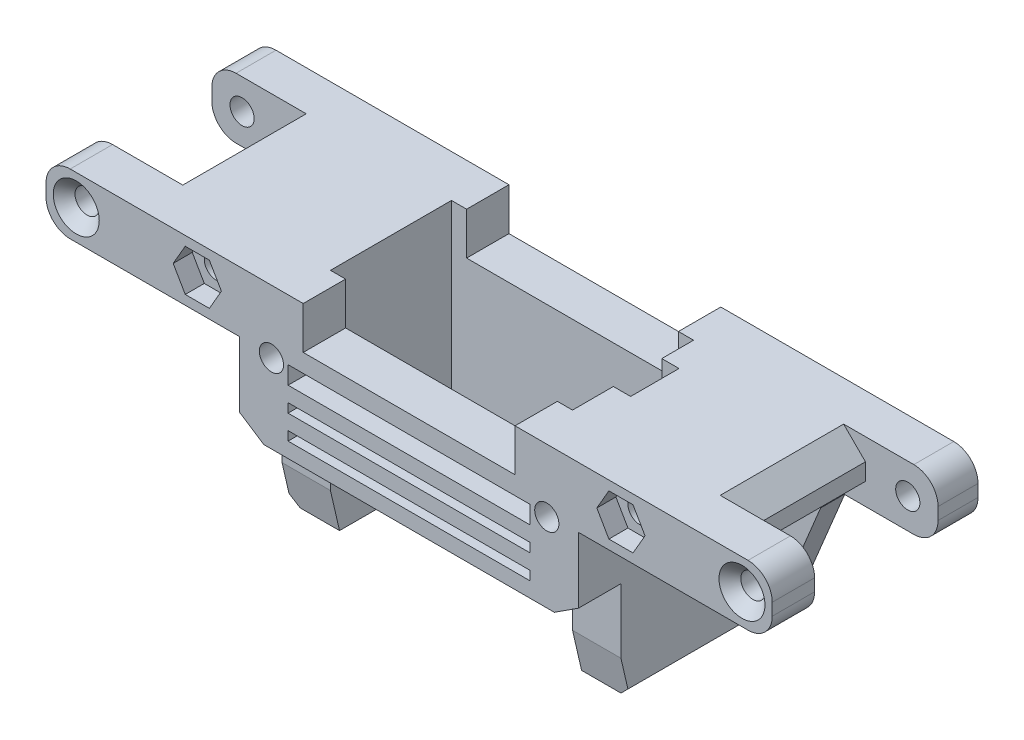
SolidWorks part; units mm, degrees
ref_plane "Front Plane" through (0, 0, 0) normal (0, 0, 1) x (1, 0, 0)
ref_plane "Top Plane" through (0, 0, 0) normal (0, 1, 0) x (1, 0, 0)
ref_plane "Right Plane" through (0, 0, 0) normal (1, 0, 0) x (0, 0, -1)
sketch "Sketch1" plane through (0, 0, 0) normal (0, 1, 0) x (1, 0, 0)
  line L0 (-60, 17) -> (-60, 10)
  line L1 (-60, 10) -> (-28, 10)
  line L2 (-28, 10) -> (-28, -10)
  line L3 (-28, 0) -> (-20, 0)
  line L4 (-20, -10) -> (-20, 10)
  line L5 (-20, 10) -> (20, 10)
  line L6 (20, 10) -> (20, -10)
  line L7 (20, 0) -> (28, 0)
  line L8 (28, -10) -> (28, 10)
  line L9 (28, 10) -> (60, 10)
  line L10 (60, 10) -> (60, 17)
  line L11 (60, 17) -> (-60, 17)
  line L12 (60, -17) -> (-60, -17)
  line L13 (60, -10) -> (60, -17)
  line L14 (28, -10) -> (60, -10)
  line L15 (-20, -10) -> (20, -10)
  line L16 (-60, -10) -> (-28, -10)
  line L17 (-60, -17) -> (-60, -10)
  point P0 (0, 10)
  point P16 (0, 17)
  dimension "D1" = 40
  dimension "D2" = 120
  dimension "D3" = 8
  dimension "D4" = 8
  dimension "D5" = 10
  dimension "D6" = 7
extrude "Boss-Extrude1" add sketch "Sketch1" along normal blind 10 contours L10 L11 L0 L1 L2 L3 L4 L5 L6 L7 L8 L9 | L17 L12 L13 L14 L8 L7 L6 L15 L4 L3 L2 L16
hole_wizard "CSK for M4 Flat Head Machine Screw1" positions "Sketch3" profile "Sketch4" countersink size "M4" standard "ANSI Metric"
sketch "Sketch3" plane through (0, 0, 17) normal (0, 0, 1) x (1, 0, 0)
  line L0 (60, 10) -> (60, 0) construction
  line L1 (-60, 10) -> (-60, 0) construction
  point P0 (-55, 5)
  point P3 (55, 5)
  point P14 (-60, 5)
  dimension "D1" = 5
  dimension "D2" = 5
sketch "Sketch4" plane through (-55, 5, 17) normal (1, 0, 0) x (0, -1, 0)
  line L0 (0, 0) -> (0, 55)
  line L1 (0, 55) -> (2, 53.7983)
  line L2 (2, 53.7983) -> (2, 1.8)
  line L3 (2, 1.8) -> (3.8, 0)
  line L5 (3.8, 0) -> (0, 0)
  line L6 (-2, 1.8) -> (-3.8, 0) construction
  line L10 (0, 55) -> (-2, 53.7983) construction
  line L11 (0, -6.35) -> (0, 107.95) construction
  dimension "Hole Dia." = 4
  dimension "Hole Depth" = 55
  dimension "Near C'Sink Dia." = 7.6
  dimension "Near C'Sink Angle" = 90
  dimension "Drill Angle" = 118
fillet "Fillet1" radius 4 8 edges at (60, 0, 13.5) (60, 10, 13.5) (60, 0, -13.5) (60, 10, -13.5) (-60, 0, -13.5) (-60, 10, -13.5) (-60, 0, 13.5) (-60, 10, 13.5)
sketch "Sketch5" plane through (0, 0, 0) normal (0, -1, 0) x (1, 0, 0)
  line L0 (-28, 10) -> (-28, -17)
  line L1 (-28, -10) -> (-28, 10) construction
  line L2 (-56, 10) -> (-28, 10) construction
  line L3 (56, -17) -> (-56, -17) construction
  line L4 (-28, -17) -> (28, -17)
  line L5 (28, -17) -> (28, 10)
  line L6 (28, 10) -> (56, 10) construction
  line L7 (28, 10) -> (28, -10) construction
  line L8 (-28, 10) -> (-20, 10)
  line L9 (-20, 10) -> (-20, -10) construction
  line L10 (-20, 10) -> (20, 10) construction
  line L11 (-20, 10) -> (-20, -10)
  line L12 (-20, -10) -> (20, -10) construction
  line L13 (-20, -10) -> (20, -10)
  line L14 (20, -10) -> (20, 10)
  line L15 (20, -10) -> (20, 10) construction
  line L16 (20, 10) -> (28, 10)
extrude "Boss-Extrude2" add sketch "Sketch5" along normal blind 28
sketch "Sketch6" plane through (0, 0, 10) normal (0, 0, 1) x (1, 0, 0)
  line L0 (-28, -28) -> (28, -28)
  line L1 (-28, -28) -> (-28, 0) construction
  line L2 (-20, -28) -> (-28, -28) construction
  line L3 (28, -28) -> (20, -28) construction
  line L4 (28, -28) -> (28, 0)
  line L5 (56, 0) -> (-56, 0) construction
  line L6 (28, -28) -> (28, 0) construction
  line L7 (28, 0) -> (20, 0)
  line L8 (20, 0) -> (20, -23.44)
  line L9 (20, -23.44) -> (-20, -23.44)
  line L10 (-20, -28) -> (-20, 0) construction
  line L11 (-20, -23.44) -> (-20, 0)
  line L12 (-20, 0) -> (-28, 0)
  line L13 (20, -28) -> (20, 0) construction
  line L14 (-28, 0) -> (-28, -28)
  line L15 (-20, -21.44) -> (20, -21.44)
  line L16 (20, -21.44) -> (20, -18.94)
  line L17 (20, -18.94) -> (-20, -18.94)
  line L18 (-20, -18.94) -> (-20, -21.44)
  line L19 (-20, -14.94) -> (-20, -17.44)
  line L20 (-20, -17.44) -> (20, -17.44)
  line L21 (20, -17.44) -> (20, -14.94)
  line L22 (20, -14.94) -> (-20, -14.94)
  line L23 (-20, -10.94) -> (-20, -13.44)
  line L24 (-20, -13.44) -> (20, -13.44)
  line L25 (20, -13.44) -> (20, -10.94)
  line L26 (20, -10.94) -> (-20, -10.94)
  line L27 (-20, -6.94) -> (-20, -9.44)
  line L28 (-20, -9.44) -> (20, -9.44)
  line L29 (20, -9.44) -> (20, -6.94)
  line L30 (20, -6.94) -> (-20, -6.94)
  line L31 (-20, -2.94) -> (-20, -5.44)
  line L32 (-20, -5.44) -> (20, -5.44)
  line L33 (20, -5.44) -> (20, -2.94)
  line L34 (20, -2.94) -> (-20, -2.94)
  dimension "D1" = 4.56
  dimension "D2" = 2
  dimension "D3" = 2.5
  dimension "D4" = 5
extrude "Boss-Extrude3" add sketch "Sketch6" along normal up to surface (7 mm away) contours L8 L17 L11 L15 | L8 L22 L11 L20 | L8 L26 L11 L24 | L8 L30 L11 L28 | L8 L34 L11 L32 up to face at (-51.2, 5, 17)
sketch "Sketch7" plane through (0, 0, -10) normal (0, 0, 1) x (1, 0, 0)
  line L0 (28, 10) -> (56, 10) construction
  line L1 (28, 10) -> (48, 10)
  line L2 (28, 10) -> (28, 0)
  line L3 (28, 0) -> (48, 0)
  line L4 (48, 10) -> (48, 0)
  line L5 (28, 10) -> (28, 0) construction
  line L6 (28, 0) -> (56, 0) construction
  line L7 (-56, 10) -> (-28, 10) construction
  line L8 (-28, 10) -> (-48, 10)
  line L9 (-28, 10) -> (-28, 0)
  line L10 (-28, 0) -> (-48, 0)
  line L11 (-48, 10) -> (-48, 0)
  line L12 (-28, 10) -> (-28, 0) construction
  line L13 (-56, 0) -> (-28, 0) construction
  dimension "D1" = 20
  dimension "D2" = 20
extrude "Boss-Extrude4" add sketch "Sketch7" along normal up to surface (20 mm away) up to face at (53, 5, 10)
chamfer "Chamfer1" distance 3.6 4 edges at (48, 0, 0) (48, 10, 0) (-48, 10, 0) (-48, 0, 0)
sketch "Sketch9" plane through (-28, 0, 0) normal (-1, 0, 0) x (0, 0, 1)
  line L0 (-13, 0) -> (-13, -28)
  line L1 (17, 0) -> (-17, 0) construction
  line L2 (17, -28) -> (-17, -28) construction
  line L3 (-13, -28) -> (-17, -28)
  line L4 (-17, -28) -> (-17, 0) construction
  line L5 (-17, -28) -> (-17, 0)
  line L6 (-17, 0) -> (-13, 0)
  dimension "D1" = 4
extrude "Boss-Extrude5" add sketch "Sketch9" against normal blind 76 from offset 10
chamfer "Chamfer2" distance 11.5 angle 45 2 edges at (38, -28, -15) (-38, -28, -15)
sketch "Sketch10" plane through (0, -28, 0) normal (0, -1, 0) x (1, 0, 0)
  line L0 (-28, 17) -> (-28, 10)
  line L1 (-26.5, 17) -> (26.5, 17) construction
  line L2 (-28, 10) -> (28, 10)
  line L3 (28, 10) -> (28, 17)
  line L4 (28, 17) -> (-28, 17)
  line L5 (-28, -13) -> (-28, 17) construction
  line L6 (28, 17) -> (28, -13) construction
  line L7 (-20, 10) -> (20, 10) construction
extrude "Cut-Extrude1" cut sketch "Sketch10" against normal up to surface (14.56 mm away) up to face at (0, -13.44, 13.5)
chamfer "Chamfer3" distance 1.5 angle 77 2 edges at (23.25, -28, 10) (-23.25, -28, 10)
hole_wizard "CSK for M4 Flat Head Machine Screw2" positions "Sketch11" profile "Sketch12" countersink size "M4" standard "ANSI Metric"
sketch "Sketch11" plane through (-695.683, 1385.2473, -21) normal (0, 0, -1) x (-1, 0, 0)
  point P0 (-730.683, -1380.2473)
  point P2 (-660.683, -1380.2473)
sketch "Sketch12" plane through (35, 5, -21) normal (1, 0, 0) x (0, 1, 0)
  line L0 (0, 0) -> (0, 40)
  line L1 (0, 40) -> (2, 38.7983)
  line L2 (2, 38.7983) -> (2, 1.95)
  line L3 (2, 1.95) -> (3.95, 0)
  line L4 (3.95, 0) -> (0, 0)
  line L5 (-2, 1.95) -> (-3.95, 0) construction
  line L6 (0, 40) -> (-2, 38.7983) construction
  line L7 (0, -6.35) -> (0, 107.95) construction
  dimension "Hole Dia." = 4
  dimension "Hole Depth" = 40
  dimension "Near C'Sink Dia." = 7.9
  dimension "Near C'Sink Angle" = 90
  dimension "Drill Angle" = 118
sketch "Sketch13" plane through (0, 0, 17) normal (0, 0, 1) x (1, 0, 0)
  line L0 (56, 10) -> (-56, 10) construction
  line L1 (-31.0163, 5) -> (-33.0081, 8.45)
  line L2 (-33.0081, 8.45) -> (-36.9919, 8.45)
  line L3 (-36.9919, 8.45) -> (-38.9837, 5)
  line L4 (-38.9837, 5) -> (-36.9919, 1.55)
  line L5 (-36.9919, 1.55) -> (-33.0081, 1.55)
  line L6 (-33.0081, 1.55) -> (-31.0163, 5)
  line L7 (38.9837, 5) -> (36.9919, 8.45)
  line L8 (36.9919, 8.45) -> (33.0081, 8.45)
  line L9 (33.0081, 8.45) -> (31.0163, 5)
  line L10 (31.0163, 5) -> (33.0081, 1.55)
  line L11 (33.0081, 1.55) -> (36.9919, 1.55)
  line L12 (36.9919, 1.55) -> (38.9837, 5)
  circle A0 centre (-35, 5) radius 3.45 construction
  circle A1 centre (35, 5) radius 3.45 construction
  dimension "D1" = 6.9
  dimension "D2" = 6.9
extrude "Cut-Extrude2" cut sketch "Sketch13" against normal blind 3.15
hole_wizard "Ø1.0mm Dowel Hole1" positions "Sketch14" profile "Sketch15" hole size "Ø1.0" standard "ANSI Metric"
sketch "Sketch14" plane through (0, -28, 0) normal (0, -1, 0) x (-1, 0, 0)
  point P0 (-24.135, 4.858)
  point P3 (-24.135, -5.048)
  point P6 (24.015, -5.048)
  point P9 (24.015, 4.858)
sketch "Sketch15" plane through (24.135, -28, -4.858) normal (1, 0, 0) x (0, 0, -1)
  line L0 (0, 0) -> (0, 13.5)
  line L1 (0, 13.5) -> (1.5, 12.5987)
  line L2 (1.5, 12.5987) -> (1.5, 0)
  line L5 (1.5, 0) -> (0, 0)
  line L10 (0, 13.5) -> (-1.5, 12.5987) construction
  line L11 (0, -6.35) -> (0, 107.95) construction
  dimension "Hole Dia." = 3
  dimension "Hole Depth" = 13.5
  dimension "Drill Angle" = 118
chamfer "Chamfer4" distance 10 2 edges at (-38, -16.5, -15) (38, -16.5, -15)
sketch "Sketch16" plane through (0, 0, -17) normal (0, 0, -1) x (-1, 0, 0)
  line L0 (38, 0) -> (56, 0) construction
  line L1 (51.0163, 5) -> (53.0081, 1.55)
  line L2 (53.0081, 1.55) -> (56.9919, 1.55)
  line L3 (56.9919, 1.55) -> (58.9837, 5)
  line L4 (58.9837, 5) -> (56.9919, 8.45)
  line L5 (56.9919, 8.45) -> (53.0081, 8.45)
  line L6 (53.0081, 8.45) -> (51.0163, 5)
  line L7 (-51.0163, 5) -> (-53.0081, 8.45)
  line L8 (-53.0081, 8.45) -> (-56.9919, 8.45)
  line L9 (-56.9919, 8.45) -> (-58.9837, 5)
  line L10 (-58.9837, 5) -> (-56.9919, 1.55)
  line L11 (-56.9919, 1.55) -> (-53.0081, 1.55)
  line L12 (-53.0081, 1.55) -> (-51.0163, 5)
  line L13 (-56, 0) -> (-38, 0) construction
  circle A0 centre (55, 5) radius 3.45 construction
  circle A1 centre (-55, 5) radius 3.45 construction
  dimension "D1" = 6.9
  dimension "D2" = 6.9
extrude "Cut-Extrude3" cut sketch "Sketch16" against normal blind 3.15
sketch "Sketch17" plane through (0, -28, 0) normal (0, -1, 0) x (1, 0, 0)
  line L0 (20, 8.5) -> (20, -10) construction
  line L1 (17.15, 3.25) -> (22.85, 3.25)
  line L2 (17.15, 3.25) -> (17.15, -4.75)
  line L3 (17.15, -4.75) -> (22.85, -4.75)
  line L4 (22.85, 3.25) -> (22.85, -4.75)
  line L5 (17.15, 3.25) -> (22.85, -4.75) construction
  line L6 (17.15, -4.75) -> (22.85, 3.25) construction
  point P0 (20, -0.75)
  dimension "D1" = 8
  dimension "D2" = 5.7
extrude "Cut-Extrude4" cut sketch "Sketch17" against normal blind 42
sketch "Sketch18" plane through (0, 0, 17) normal (0, 0, 1) x (1, 0, 0)
  line L0 (56, 10) -> (-56, 10) construction
  line L1 (-17.5, 3) -> (17.5, 3)
  line L2 (-17.5, 3) -> (-17.5, 17)
  line L3 (-17.5, 17) -> (17.5, 17)
  line L4 (17.5, 3) -> (17.5, 17)
  line L5 (-17.5, 3) -> (17.5, 17) construction
  line L6 (-17.5, 17) -> (17.5, 3) construction
  line L7 (-15.63, 0) -> (15.75, 0) construction
  point P0 (0, 10)
  dimension "D1" = 3
  dimension "D2" = 35
extrude "Cut-Extrude5" cut sketch "Sketch18" against normal through all both and the other way through all
extrude "Cut-Extrude6" cut sketch "Sketch19" against normal blind 15
sketch "Sketch19" plane through (-695.683, 1385.2473, 25) normal (0, 0, 1) x (1, 0, 0)
  line L1 (667.683, -1396.0897) -> (667.683, -1398.6873)
  line L4 (667.683, -1398.6873) -> (671.683, -1398.6873)
  line L6 (671.683, -1398.6873) -> (667.683, -1396.0897)
  line L7 (719.683, -1398.6873) -> (723.683, -1398.6873)
  line L8 (723.683, -1398.6873) -> (723.683, -1396.0897)
  line L11 (723.683, -1396.0897) -> (719.683, -1398.6873)
hole_wizard "CSK for M4 SFHCS2" positions "Sketch22" profile "Sketch23" countersink size "M4" standard "ANSI Metric"
sketch "Sketch22" plane through (-695.683, 1385.2473, -10) normal (0, 0, 1) x (1, 0, 0)
  point P0 (681.183, -1407.7473)
  point P3 (710.183, -1407.7473)
sketch "Sketch23" plane through (-14.5, -22.5, -10) normal (1, 0, 0) x (0, -1, 0)
  line L0 (0, 0) -> (0, 12.2017)
  line L1 (0, 12.2017) -> (2, 11)
  line L2 (2, 11) -> (2, 1.8)
  line L3 (2, 1.8) -> (3.8, 0)
  line L4 (3.8, 0) -> (0, 0)
  line L5 (-2, 1.8) -> (-3.8, 0) construction
  line L6 (0, 12.2017) -> (-2, 11) construction
  line L7 (0, -6.35) -> (0, 107.95) construction
  dimension "Hole Dia." = 4
  dimension "Hole Depth" = 11
  dimension "Near C'Sink Dia." = 7.6
  dimension "Near C'Sink Angle" = 90
  dimension "Drill Angle" = 118
hole_wizard "CSK for M4 SFHCS3" positions "Sketch24" profile "Sketch25" countersink size "M4" standard "ANSI Metric"
sketch "Sketch24" plane through (-695.683, 1385.2473, 25) normal (0, 0, 1) x (1, 0, 0)
  point P0 (672.933, -1385.6685)
  point P2 (718.433, -1385.6685)
sketch "Sketch25" plane through (-22.75, -0.4212, 25) normal (1, 0, 0) x (0, -1, 0)
  line L0 (0, 0) -> (0, 17.2017)
  line L1 (0, 17.2017) -> (2, 16)
  line L2 (2, 16) -> (2, 1.95)
  line L3 (2, 1.95) -> (3.95, 0)
  line L4 (3.95, 0) -> (0, 0)
  line L5 (-2, 1.95) -> (-3.95, 0) construction
  line L6 (0, 17.2017) -> (-2, 16) construction
  line L7 (0, -6.35) -> (0, 107.95) construction
  dimension "Hole Dia." = 4
  dimension "Hole Depth" = 16
  dimension "Near C'Sink Dia." = 7.9
  dimension "Near C'Sink Angle" = 90
  dimension "Drill Angle" = 118
sketch "Sketch26" plane through (0, 0, -10) normal (0, 0, 1) x (1, 0, 0)
  line L6 (-48, 3.6) -> (-48, 6.4)
  line L7 (-48, 6.4) -> (-44.4, 10)
  line L8 (-44.4, 10) -> (-56, 10)
  line L9 (-60, 6) -> (-60, 4)
  line L10 (-56, 0) -> (-44.4, 0)
  line L11 (-44.4, 0) -> (-48, 3.6)
  line L12 (-48, 3.6) -> (-48, 6.4)
  line L13 (-48, 6.4) -> (-44.4, 10)
  line L14 (-44.4, 10) -> (-56, 10)
  line L15 (-60, 6) -> (-60, 4)
  line L16 (-56, 0) -> (-44.4, 0)
  line L17 (-44.4, 0) -> (-48, 3.6)
  line L18 (48, 6.4) -> (48, 3.6)
  line L19 (48, 3.6) -> (44.4, 0)
  line L20 (44.4, 0) -> (56, 0)
  line L21 (60, 4) -> (60, 6)
  line L22 (56, 10) -> (44.4, 10)
  line L23 (44.4, 10) -> (48, 6.4)
  line L24 (48, 6.4) -> (48, 3.6)
  line L25 (48, 3.6) -> (44.4, 0)
  line L26 (44.4, 0) -> (56, 0)
  line L27 (60, 4) -> (60, 6)
  line L28 (56, 10) -> (44.4, 10)
  line L29 (44.4, 10) -> (48, 6.4)
  arc A2 (-56, 10) -> (-60, 6) centre (-56, 6) ccw
  arc A3 (-60, 4) -> (-56, 0) centre (-56, 4) ccw
  arc A4 (-56, 10) -> (-60, 6) centre (-56, 6) ccw
  arc A5 (-60, 4) -> (-56, 0) centre (-56, 4) ccw
  arc A6 (56, 0) -> (60, 4) centre (56, 4) ccw
  arc A7 (60, 6) -> (56, 10) centre (56, 6) ccw
  arc A8 (56, 0) -> (60, 4) centre (56, 4) ccw
  arc A9 (60, 6) -> (56, 10) centre (56, 6) ccw
  dimension "D1" = 0
  dimension "D2" = 0
extrude "Cut-Extrude7" cut sketch "Sketch26" against normal blind 0.4
